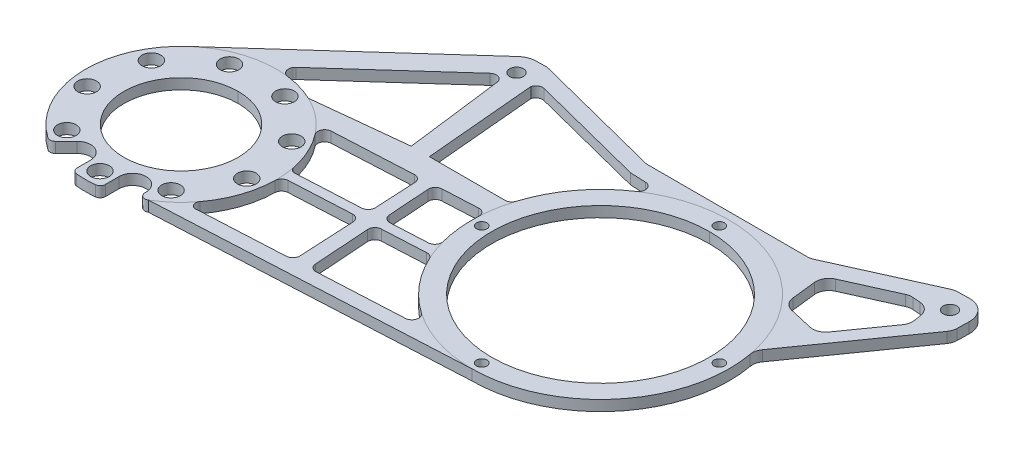
SolidWorks part; units mm, degrees
material "6061-T6 (SS)"
ref_plane "Front Plane" through (0, 0, 0) normal (0, 0, 1) x (1, 0, 0)
ref_plane "Top Plane" through (0, 0, 0) normal (0, 1, 0) x (1, 0, 0)
ref_plane "Right Plane" through (0, 0, 0) normal (1, 0, 0) x (0, 0, -1)
sketch "Sketch3" plane through (0, 0, 0) normal (0, 1, 0) x (-1, 0, 0)
  line L0 (-49.4271, 17.6796) -> (34.1123, 92.8183)
  line L1 (-168.4036, 158.864) -> (-20.3196, 166.4019)
  line L3 (-268.4562, 19.3463) -> (-265.179, 163.648)
  line L4 (-265.179, 163.648) -> (-168.4036, 158.864)
  line L5 (-258.9312, 9.8213) -> (-55.7968, 15.2364)
  line L8 (26.5678, 164.3167) -> (21.3029, 159.0518)
  line L9 (10.2067, 163.648) -> (10.2067, 170.2207)
  line L10 (-3.4709, 170.2207) -> (-3.4709, 163.648)
  line L11 (-16.4709, 163.648) -> (-16.4709, 164.225)
  circle A0 centre (-258.9312, 19.3463) radius 3.3
  circle A1 centre (-258.9312, 19.3463) radius 9.525
  circle A2 centre (-55.7968, 24.7614) radius 9.525
  circle A3 centre (3.3679, 127) radius 27.4955
  arc A16 (-20.3196, 166.4019) -> (29.8256, 164.5979) centre (3.3679, 127) ccw
  arc A17 (29.8256, 164.5979) -> (26.5678, 164.3167) centre (28.3638, 162.5207) ccw
  arc A18 (10.2067, 163.648) -> (21.3029, 159.0518) centre (16.7067, 163.648) ccw
  arc A19 (10.2067, 170.2207) -> (7.9181, 172.7483) centre (7.6667, 170.2207) ccw
  arc A20 (7.9181, 172.7483) -> (-1.1823, 172.7483) centre (3.3679, 127) ccw
  arc A21 (-1.1823, 172.7483) -> (-3.4709, 170.2207) centre (-0.9309, 170.2207) ccw
  arc A22 (-16.4709, 163.648) -> (-3.4709, 163.648) centre (-9.9709, 163.648) ccw
  arc A23 (-16.4709, 164.225) -> (-20.3196, 166.4019) centre (-19.0109, 164.225) ccw
  circle A26 centre (-168.4036, 96.9515) radius 61.9125
  circle A27 centre (-168.4036, 96.9515) radius 52.3875
  arc A30 (-52.5573, 25.3906) -> (-59.0363, 24.1323) centre (-55.7968, 24.7614) ccw
  arc A31 (-59.0363, 24.1323) -> (-52.5573, 25.3906) centre (-55.7968, 24.7614) ccw
  arc A32 (-47.1642, 28.7869) -> (-65.1471, 22.9455) centre (-55.7968, 24.7614) ccw
  arc A35 (-251.1288, 13.883) -> (-265.179, 26.536) centre (-258.9312, 19.3463) ccw
  circle A45 centre (-9.9709, 90.352) radius 4.5
  circle A46 centre (16.7067, 90.352) radius 4.5
  circle A47 centre (37.1429, 107.5) radius 4.5
  circle A48 centre (41.7754, 133.7723) radius 4.5
  circle A49 centre (28.4366, 156.8757) radius 4.5
  circle A50 centre (3.3679, 166) radius 4.5
  circle A51 centre (-21.7008, 156.8757) radius 4.5
  circle A52 centre (-35.0396, 133.7723) radius 4.5
  circle A53 centre (-30.4071, 107.5) radius 4.5
  circle A59 centre (-111.2536, 96.9515) radius 2.5
  circle A60 centre (-225.5536, 96.9515) radius 2.5
  circle A61 centre (-168.4036, 39.8015) radius 2.5
  arc A62 (-168.4036, 151.6015) -> (-168.4036, 156.6015) centre (-168.4036, 154.1015) ccw
  arc A63 (-168.4036, 156.6015) -> (-168.4036, 151.6015) centre (-168.4036, 154.1015) ccw
  circle A66 centre (-111.5667, 90.9777) radius 2.5
  circle A67 centre (-225.2405, 90.9777) radius 2.5
  dimension "D1" = 3.3
  dimension "D2" = 6.6
  dimension "D3" = 54.991
extrude "Boss-Extrude1" add sketch "Sketch3" along normal blind 5.08
sketch "Sketch4" plane through (0, 5.08, 0) normal (0, 1, 0) x (1, 0, 0)
  circle A0 centre (-3.3679, -127) radius 27.4955 construction
  circle A1 centre (168.4036, -96.9515) radius 52.3875 construction
  circle A2 centre (-3.3679, -127) radius 27.4955
  circle A3 centre (168.4036, -96.9515) radius 52.3875
sketch "Sketch5" plane through (0, 5.08, 0) normal (0, 1, 0) x (1, 0, 0)
  line L0 (-3.3679, -99.5045) -> (-3.3679, -154.4955)
  line L1 (-3.3679, -127) -> (-3.3679, -1127) construction
  circle A0 centre (-3.3679, -127) radius 27.4955 construction
split line "Split Line1"
sketch "Sketch6" plane through (0, 5.08, 0) normal (0, 1, 0) x (1, 0, 0)
  line L0 (168.4036, -44.564) -> (168.4036, -149.339)
  line L1 (168.4036, -96.9515) -> (168.4036, -1096.9515) construction
  circle A0 centre (168.4036, -96.9515) radius 52.3875 construction
split line "Split Line2"
sketch "Sketch7" plane through (0, 5.08, 0) normal (0, 1, 0) x (1, 0, 0)
  circle A0 centre (-3.3679, -127) radius 45.974
  arc A1 (-34.1123, -92.8183) -> (-29.8256, -164.5979) centre (-3.3679, -127) ccw construction
split line "Split Line3"
sketch "Sketch8" plane through (0, 5.08, 0) normal (0, 1, 0) x (1, 0, 0)
  circle A0 centre (168.4036, -96.9515) radius 61.9125
  dimension "D1" = 123.825
split line "Split Line4"
sketch "Sketch12" plane through (0, 5.08, 0) normal (0, 1, 0) x (1, 0, 0)
  line L0 (268.4464, -19.7788) -> (265.179, -163.648) construction
  line L1 (265.179, -163.648) -> (168.4036, -158.864) construction
  line L2 (268.2736, -27.3857) -> (265.179, -163.648)
  line L3 (265.179, -163.648) -> (168.4036, -158.864)
  line L4 (230.3161, -96.9515) -> (267.9756, -40.5087)
  line L5 (268.2736, -27.3857) -> (228.7924, -83.3003)
  circle A0 centre (168.4036, -96.9515) radius 61.9125 construction
  arc A1 (168.4036, -158.864) -> (228.7924, -83.3003) centre (168.4036, -96.9515) ccw
  circle M5 centre (168.4036, -96.9515) radius 61.9125
  line M6 (168.4036, -158.864) -> (265.179, -163.648)
  line M7 (265.179, -163.648) -> (268.4464, -19.7788)
extrude "Cut-Extrude3" cut sketch "Sketch12" against normal up to next contours L4 M5 M6 M7 | L2 L5 L4 M5
sketch "Sketch13" plane through (0, 5.08, 0) normal (0, 1, 0) x (1, 0, 0)
  line L0 (258.9312, -9.8213) -> (258.4237, -9.8349)
  line L1 (258.4237, -9.8349) -> (55.7968, -15.2364) construction
  line L2 (251.7189, -10.0136) -> (203.8333, -31.5488)
  line L3 (203.8333, -31.5488) -> (125.0432, -31.5488)
  line L4 (125.0432, -31.5488) -> (60.8149, -15.1026)
  line L5 (251.7189, -10.0136) -> (60.8149, -15.1026)
  circle A0 centre (258.9312, -19.3463) radius 9.525
  line M9 (258.4237, -9.8349) -> (55.7968, -15.2364)
extrude "Cut-Extrude4" cut sketch "Sketch13" against normal up to next contours L4 L3 L2 M9
sketch "Sketch14" plane through (0, 5.08, 0) normal (0, 1, 0) x (1, 0, 0)
  line L0 (239.0242, -57.6592) -> (253.6581, -36.9341)
  line L1 (254.7489, -32.3175) -> (254.2025, -28.7219)
  line L3 (248.4154, -23.3448) -> (244.7894, -23.0637)
  line L4 (241.6941, -23.6034) -> (218.5554, -34.0093)
  line L5 (214.8502, -40.5152) -> (216.1624, -52.1017)
  line L6 (221.0511, -57.5762) -> (232.4161, -60.1855)
  line L7 (251.7189, -10.0136) -> (203.8333, -31.5488) construction
  line L10 (268.2736, -27.3857) -> (228.7924, -83.3003) construction
  arc A0 (253.6581, -36.9341) -> (254.7489, -32.3175) centre (248.4709, -33.2715) ccw
  arc A1 (232.4161, -60.1855) -> (239.0242, -57.6592) centre (233.837, -53.9965) ccw
  arc A2 (221.0511, -57.5762) -> (216.1624, -52.1017) centre (222.4721, -51.3872) cw
  arc A3 (218.5554, -34.0093) -> (214.8502, -40.5152) centre (221.1599, -39.8006) ccw
  arc A4 (241.6941, -23.6034) -> (244.7894, -23.0637) centre (244.2985, -29.3947) cw
  arc A5 (248.4154, -23.3448) -> (254.2025, -28.7219) centre (247.9245, -29.6758) cw
  dimension "D1" = 6.35
extrude "Cut-Extrude5" cut sketch "Sketch14" against normal up to next
sketch "Sketch16" plane through (0, 5.08, 0) normal (0, 1, 0) x (1, 0, 0)
  line L0 (0.4703, -75.6413) -> (49.6646, -31.3939)
  line L3 (49.4271, -17.6796) -> (-34.1123, -92.8183) construction
  line L4 (69.0462, -24.7278) -> (125.0432, -39.0662)
  line L7 (61.1192, -80.7261) -> (16.3849, -85.4857)
  line L9 (104.9029, -80.7261) -> (106.1813, -80.7261)
  line L10 (125.0432, -31.5488) -> (60.8149, -15.1026) construction
  line L11 (125.0432, -31.5488) -> (125.0432, -39.0662) construction
  line L12 (125.0432, -39.0662) -> (132.4333, -39.3334)
  line L13 (61.1192, -80.7261) -> (55.1748, -33.8488)
  line L14 (55.1748, -33.8488) -> (65.0273, -27.1118)
  line L15 (104.9029, -80.7261) -> (69.8369, -80.7261)
  line L16 (69.8369, -80.7261) -> (65.0273, -27.1118)
  arc A0 (228.7924, -83.3003) -> (106.7642, -91.1427) centre (168.4036, -96.9515) ccw construction
  arc A1 (134.1413, -45.3835) -> (109.3318, -78.4129) centre (168.4036, -96.9515) ccw
  arc A2 (31.0995, -96.5762) -> (-34.1123, -92.8183) centre (-3.3679, -127) ccw construction
  arc A3 (16.3849, -85.4857) -> (2.2733, -81.3734) centre (-3.3679, -127) ccw
  arc A6 (0.4703, -75.6413) -> (2.2733, -81.3734) centre (2.6784, -78.0964) ccw
  arc A7 (134.1413, -45.3835) -> (132.4333, -39.3334) centre (132.314, -42.6333) ccw
  arc A8 (109.3318, -78.4129) -> (106.1813, -80.7261) centre (106.1813, -77.4241) cw
  arc A11 (49.6646, -31.3939) -> (55.1748, -33.8488) centre (51.8728, -33.849) cw
  arc A12 (65.0273, -27.1118) -> (69.0462, -24.7278) centre (68.2272, -27.9265) cw
  point P29 (-5.5754, -81.079)
  point P38 (44.0746, 0.7041)
  arc M30 (-34.1123, -92.8183) -> (31.0995, -96.5762) centre (-3.3679, -127) cw
  arc M34 (106.7642, -91.1427) -> (228.7924, -83.3003) centre (168.4036, -96.9515) cw
  dimension "D1" = 3.302
  dimension "D3" = 3.302
extrude "Cut-Extrude7" cut sketch "Sketch16" against normal up to next contours A12 L16 L15 L9 A8 A7 L12 L4 M34 | A11 L0 A6 L7 L13 M30
sketch "Sketch17" plane through (0, 5.08, 0) normal (0, 1, 0) x (1, 0, 0)
  line L0 (131.4527, -153.8694) -> (90.643, -155.9468)
  line L1 (168.4036, -158.864) -> (20.3196, -166.4019) construction
  line L2 (103.1088, -90.2751) -> (86.224, -91.1346)
  line L3 (87.1812, -152.8801) -> (85.2931, -125.9611)
  line L4 (80.0529, -153.1795) -> (78.6813, -126.2343)
  line L5 (109.206, -121.3742) -> (88.4192, -122.4323)
  line L6 (105.5125, -116.8776) -> (87.9654, -117.7708)
  line L7 (84.5036, -114.7041) -> (83.0979, -94.6634)
  line L8 (78.1077, -114.9664) -> (77.0866, -94.906)
  line L9 (75.2157, -123.1044) -> (45.732, -124.6052)
  line L10 (74.9778, -118.4319) -> (44.3271, -119.9922)
  line L11 (76.923, -156.6451) -> (35.4904, -158.7542)
  line L12 (73.621, -91.7761) -> (35.564, -93.7134)
  arc A0 (20.3196, -166.4019) -> (16.3849, -85.4857) centre (-3.3679, -127) ccw construction
  arc A1 (109.3318, -78.4129) -> (168.4036, -158.864) centre (168.4036, -96.9515) ccw construction
  arc A2 (33.3335, -154.6878) -> (42.5984, -127.8424) centre (-3.3679, -127) ccw
  arc A3 (106.5742, -93.7439) -> (108.5375, -112.738) centre (168.4036, -96.9515) ccw
  arc A4 (41.7076, -117.9552) -> (33.1118, -99.0207) centre (-3.3679, -127) ccw
  arc A5 (112.3627, -123.2683) -> (133.1642, -147.8567) centre (168.4036, -96.9515) ccw
  arc A6 (105.5125, -116.8776) -> (108.5375, -112.738) centre (105.3447, -113.5799) ccw
  arc A7 (106.5742, -93.7439) -> (103.1088, -90.2751) centre (103.2767, -93.5728) ccw
  arc A8 (83.0979, -94.6634) -> (86.224, -91.1346) centre (86.3918, -94.4323) cw
  arc A9 (74.9778, -118.4319) -> (78.1077, -114.9664) centre (74.81, -115.1342) ccw
  arc A10 (84.5036, -114.7041) -> (87.9654, -117.7708) centre (87.7975, -114.4731) ccw
  arc A11 (77.0866, -94.906) -> (73.621, -91.7761) centre (73.7888, -95.0739) ccw
  arc A12 (33.1118, -99.0207) -> (35.564, -93.7134) centre (35.7318, -97.0111) cw
  arc A13 (78.6813, -126.2343) -> (75.2157, -123.1044) centre (75.3835, -126.4021) ccw
  arc A14 (131.4527, -153.8694) -> (133.1642, -147.8567) centre (131.2848, -150.5717) ccw
  arc A15 (112.3627, -123.2683) -> (109.206, -121.3742) centre (109.3739, -124.6719) ccw
  arc A16 (85.2931, -125.9611) -> (88.4192, -122.4323) centre (88.587, -125.73) cw
  arc A17 (87.1812, -152.8801) -> (90.643, -155.9468) centre (90.4751, -152.649) ccw
  arc A18 (76.923, -156.6451) -> (80.0529, -153.1795) centre (76.7551, -153.3474) ccw
  arc A19 (45.732, -124.6052) -> (42.5984, -127.8424) centre (45.8998, -127.9029) ccw
  arc A20 (35.4904, -158.7542) -> (33.3335, -154.6878) centre (35.3613, -156.2175) cw
  arc A21 (44.3271, -119.9922) -> (41.7076, -117.9552) centre (44.1979, -117.4555) cw
  point P22 (29.5883, -159.0546)
  point P30 (109.713, -116.6638)
  point P33 (106.8732, -90.0835)
  point P38 (78.2756, -118.2641)
  point P43 (76.9187, -91.6083)
  point P46 (28.7059, -94.0625)
  point P49 (78.5134, -122.9365)
  point P52 (142.7407, -153.2948)
  point P55 (111.4625, -121.2593)
  point P62 (80.2207, -156.4773)
  point P65 (42.5518, -124.7671)
  point P67 (42.0863, -120.1062)
  dimension "D1" = 3.302
  dimension "D2" = 3.302
  dimension "D3" = 2.54
  dimension "D4" = 2.54
extrude "Cut-Extrude8" cut sketch "Sketch17" against normal up to next contours L0 A17 L3 A16 L5 A15 A5 A14 | A2 A19 L9 A13 L4 A18 L11 A20 | L2 A8 L7 A10 L6 A6 A3 A7 | A4 A12 L12 A11 L8 A9 L10 A21
fillet "Fillet1" radius 6.35 5 edges at (125.0432, 2.54, 31.5488) (251.7189, 2.54, 10.0136) (203.8333, 2.54, 31.5488) (268.2736, 2.54, 27.3857) (228.7924, 2.54, 83.3003)
